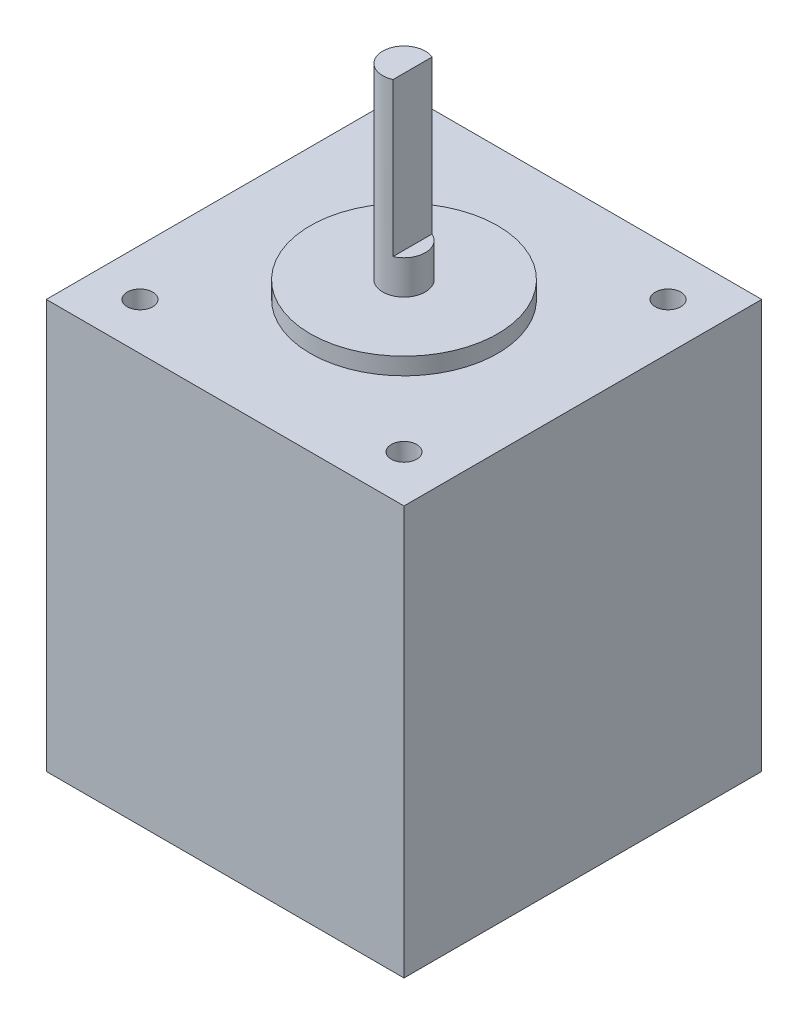
SolidWorks part; units mm, degrees
ref_plane "前视基准面" through (0, 0, 0) normal (0, 0, 1) x (1, 0, 0)
ref_plane "上视基准面" through (0, 0, 0) normal (0, 1, 0) x (1, 0, 0)
ref_plane "右视基准面" through (0, 0, 0) normal (1, 0, 0) x (0, 0, -1)
sketch "草图1" plane through (0, 0, 0) normal (0, 1, 0) x (1, 0, 0)
  line L1 (0, 0) -> (42, 0)
  line L2 (0, 0) -> (0, 42)
  line L3 (0, 42) -> (42, 42)
  line L4 (42, 0) -> (42, 42)
extrude "凸台-拉伸1" add sketch "草图1" along normal blind 48
sketch "草图2" plane through (0, 48, 0) normal (0, 1, 0) x (1, 0, 0)
  line L0 (21, 0) -> (21, 21)
  line L1 (0, 0) -> (42, 0) construction
  circle A0 centre (21, 21) radius 11
extrude "凸台-拉伸2" add sketch "草图2" along normal blind 2
sketch "草图3" plane through (0, 0, 0) normal (0, -1, 0) x (1, 0, 0)
  line L0 (21, -42) -> (21, -21)
  line L1 (42, -42) -> (0, -42) construction
  line L2 (21, -21) -> (36.5, -21)
  line L3 (36.5, -21) -> (36.5, -5.5)
  line L4 (36.5, -5.5) -> (5.5, -5.5)
  line L5 (5.5, -5.5) -> (5.5, -36.5)
  line L6 (5.5, -36.5) -> (36.5, -36.5)
  circle A0 centre (36.5, -5.5) radius 1.5
  circle A1 centre (5.5, -5.5) radius 1.5
  circle A2 centre (5.5, -36.5) radius 1.5
  circle A3 centre (36.5, -36.5) radius 1.5
extrude "切除-拉伸1" cut sketch "草图3" against normal through all contours A2 | A1 | A0 | A3
sketch "草图4" plane through (0, 50, 0) normal (0, 1, 0) x (1, 0, 0)
  circle A0 centre (21, 21) radius 2.5
extrude "凸台-拉伸3" add sketch "草图4" along normal blind 22
sketch "草图5" plane through (0, 72, 0) normal (0, 1, 0) x (1, 0, 0)
  line L0 (18.5, 21) -> (22, 21)
  line L1 (22, 18.7087) -> (22, 23.2913)
  circle A0 centre (21, 21) radius 2.5 construction
  circle A1 centre (21, 21) radius 2.5 construction
  circle A2 centre (21, 21) radius 2.5
  circle M3 centre (21, 21) radius 2.5
extrude "切除-拉伸2" cut sketch "草图5" against normal blind 18 contours L1 M3
